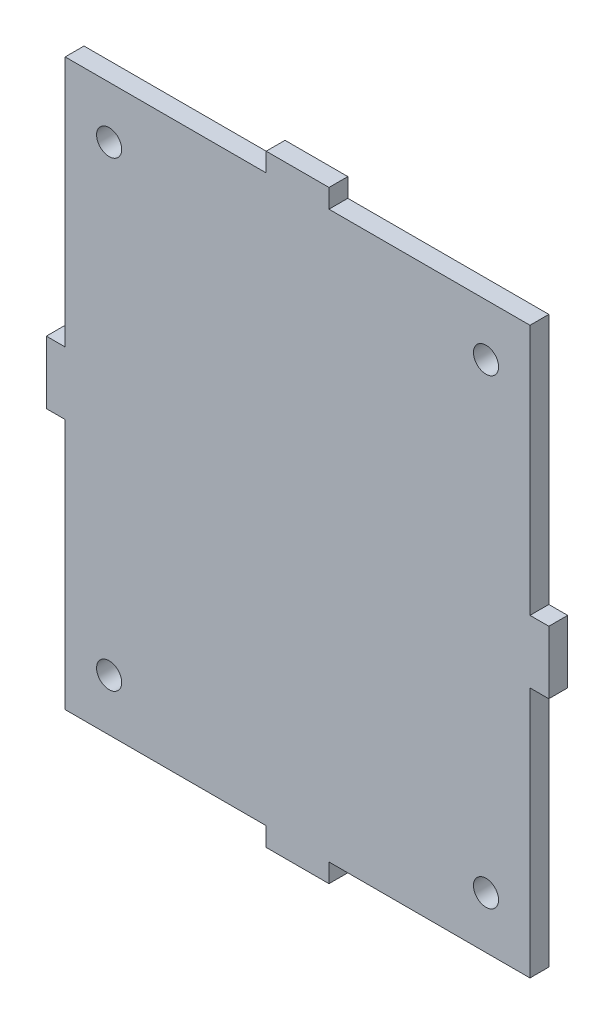
SolidWorks part; units mm, degrees
ref_plane "Front Plane" through (0, 0, 0) normal (0, 0, 1) x (1, 0, 0)
ref_plane "Top Plane" through (0, 0, 0) normal (0, 1, 0) x (1, 0, 0)
ref_plane "Right Plane" through (0, 0, 0) normal (1, 0, 0) x (0, 0, -1)
sketch "Sketch1" plane through (0, 0, 0) normal (0, 0, 1) x (1, 0, 0)
  line L0 (5, 8.25) -> (40, 8.25)
  line L5 (0, 0) -> (28.5, 0) construction
  line L6 (-5, 11.25) -> (5, 11.25)
  line L7 (28.5, 0) -> (30, 0) construction
  line L8 (0, 0) -> (0, -15.5615) construction
  line L9 (30, -2) -> (30, -71.5) construction
  line L10 (30, -36.75) -> (0, -36.75) construction
  line L11 (28.5, -73.5) -> (30, -73.5) construction
  line L12 (-5, 11.25) -> (-5, 8.25)
  line L13 (0, -73.5) -> (28.5, -73.5) construction
  line L14 (-28.5, -73.5) -> (-30, -73.5) construction
  line L15 (-30, -2) -> (-30, -71.5) construction
  line L16 (-28.5, 0) -> (-30, 0) construction
  line L18 (-40, -81.75) -> (-5, -81.75)
  line L19 (-40, -81.75) -> (-40, -41.75)
  line L20 (-40, 8.25) -> (-5, 8.25)
  line L21 (40, -81.75) -> (40, -41.75)
  line L22 (-40, -81.75) -> (40, 8.25) construction
  line L23 (-40, 8.25) -> (40, -81.75) construction
  line L24 (5, 11.25) -> (5, 8.25)
  line L25 (5, -84.75) -> (5, -81.75)
  line L26 (-5, -84.75) -> (-5, -81.75)
  line L27 (-5, -84.75) -> (5, -84.75)
  line L28 (5, -81.75) -> (40, -81.75)
  line L29 (40, -31.75) -> (40, 8.25)
  line L30 (37, -41.75) -> (40, -41.75)
  line L31 (37, -41.75) -> (37, -31.75)
  line L32 (37, -31.75) -> (40, -31.75)
  line L34 (-37, -31.75) -> (-40, -31.75)
  line L35 (-37, -41.75) -> (-37, -31.75)
  line L36 (-37, -41.75) -> (-40, -41.75)
  line L37 (-40, -31.75) -> (-40, 8.25)
  circle A0 centre (30, 0) radius 2
  circle A1 centre (30, -73.5) radius 2
  circle A2 centre (-30, -73.5) radius 2
  circle A3 centre (-30, 0) radius 2
  point P0 (0, 0)
  point P1 (0, 8.25)
  point P36 (0, -81.75)
  point P37 (40, -36.75)
  point P46 (-40, -36.75)
  dimension "D2" = 4
  dimension "D1" = 28.5
extrude "Boss-Extrude1" add sketch "Sketch1" along normal blind 3
sketch "Sketch2" plane through (0, 0, 3) normal (0, 0, 1) x (1, 0, 0)
  line L0 (0, 11.25) -> (0, -84.75) construction
  line L1 (5, 11.25) -> (-5, 11.25) construction
  line L2 (-5, -84.75) -> (5, -84.75) construction
  line L3 (5, 11.25) -> (40, 11.25) construction
  line L4 (40, -84.75) -> (37, -84.75)
  line L5 (40, -84.75) -> (40, 11.25)
  line L6 (40, 11.25) -> (37, 11.25)
  line L7 (37, -84.75) -> (37, 11.25)
  line L8 (-37, -84.75) -> (-37, 11.25)
  line L9 (-40, 11.25) -> (-37, 11.25)
  line L10 (-40, -84.75) -> (-40, 11.25)
  line L11 (-40, -84.75) -> (-37, -84.75)
extrude "Cut-Extrude1" cut sketch "Sketch2" against normal blind 10
sketch "Sketch3" plane through (0, 0, 3) normal (0, 0, 1) x (1, 0, 0)
  line L0 (40, -31.75) -> (40, -41.75) construction
  line L1 (40, -31.75) -> (40, -41.75)
  line L2 (40, -41.75) -> (37, -41.75)
  line L4 (40, -31.75) -> (37, -31.75)
  line L5 (37, -41.75) -> (37, -31.75)
  line L6 (40, -36.75) -> (37, -31.75) construction
  line L7 (40, -36.75) -> (37, -41.75) construction
  line L8 (0, 11.25) -> (0, -84.75) construction
  line L9 (5, 11.25) -> (-5, 11.25) construction
  line L10 (-5, -84.75) -> (5, -84.75) construction
  line L11 (-40, -36.75) -> (-37, -41.75) construction
  line L12 (-40, -36.75) -> (-37, -31.75) construction
  line L13 (-40, -31.75) -> (-40, -41.75) construction
  line L14 (-37, -41.75) -> (-37, -31.75)
  line L15 (-40, -31.75) -> (-37, -31.75)
  line L16 (-40, -41.75) -> (-37, -41.75)
  line L17 (-40, -31.75) -> (-40, -41.75)
  point P2 (40, -36.75)
  point P20 (-40, -36.75)
extrude "Boss-Extrude2" add sketch "Sketch3" against normal up to surface (3 mm away) up to face at (0, -36.75, 0)
